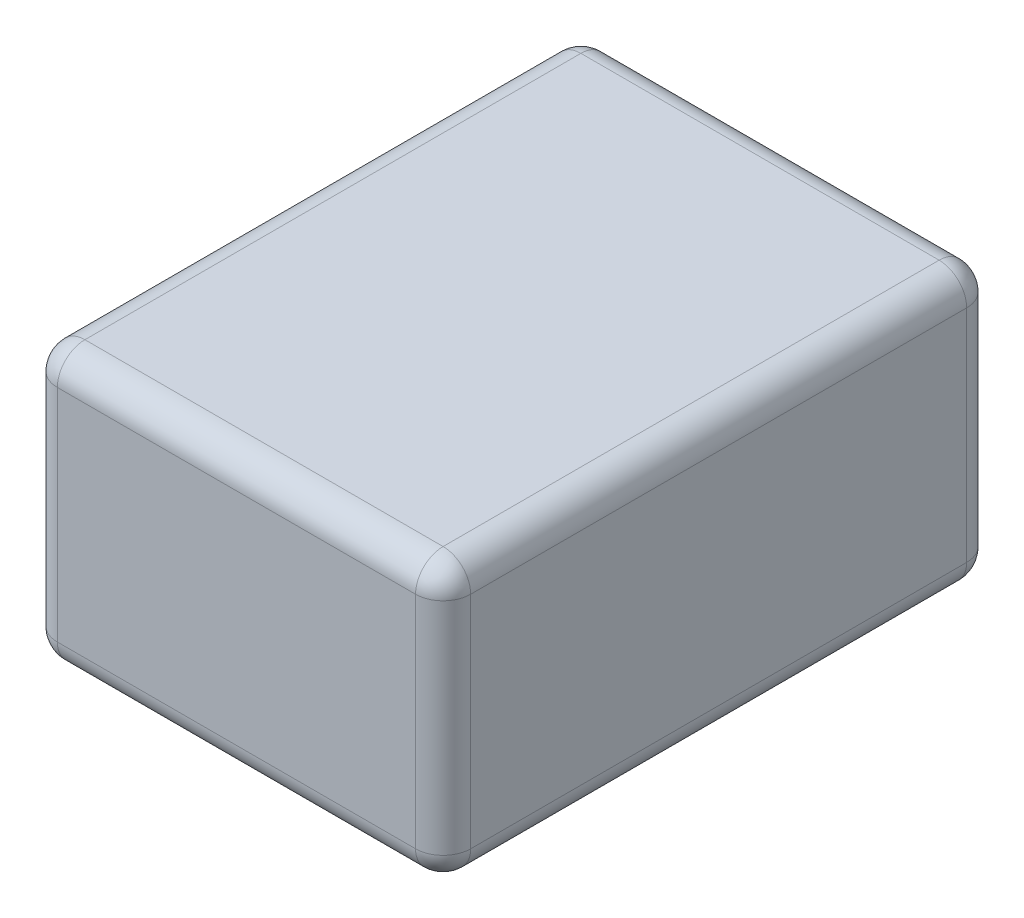
SolidWorks part; units mm, degrees
ref_plane "Front Plane" through (0, 0, 0) normal (0, 0, 1) x (1, 0, 0)
ref_plane "Top Plane" through (0, 0, 0) normal (0, 1, 0) x (1, 0, 0)
ref_plane "Right Plane" through (0, 0, 0) normal (1, 0, 0) x (0, 0, -1)
sketch "Sketch1" plane through (0, 0, 0) normal (0, 0, 1) x (1, 0, 0)
  line L1 (-15, 10) -> (15, 10)
  line L2 (-15, 10) -> (-15, -10)
  line L3 (-15, -10) -> (15, -10)
  line L4 (15, 10) -> (15, -10)
  line L5 (-15, 10) -> (15, -10) construction
  line L6 (-15, -10) -> (15, 10) construction
  point P0 (0, 0)
  dimension "D1" = 30
  dimension "D2" = 20
extrude "Boss-Extrude1" add sketch "Sketch1" along normal blind 40
fillet "Fillet1" radius 2 12 edges at (15, -10, 20) (0, -10, 40) (-15, 0, 0) (0, -10, 0) (0, 10, 0) (15, 0, 0) (15, 0, 40) (-15, -10, 20) (-15, 0, 40) (-15, 10, 20) (0, 10, 40) (15, 10, 20)
